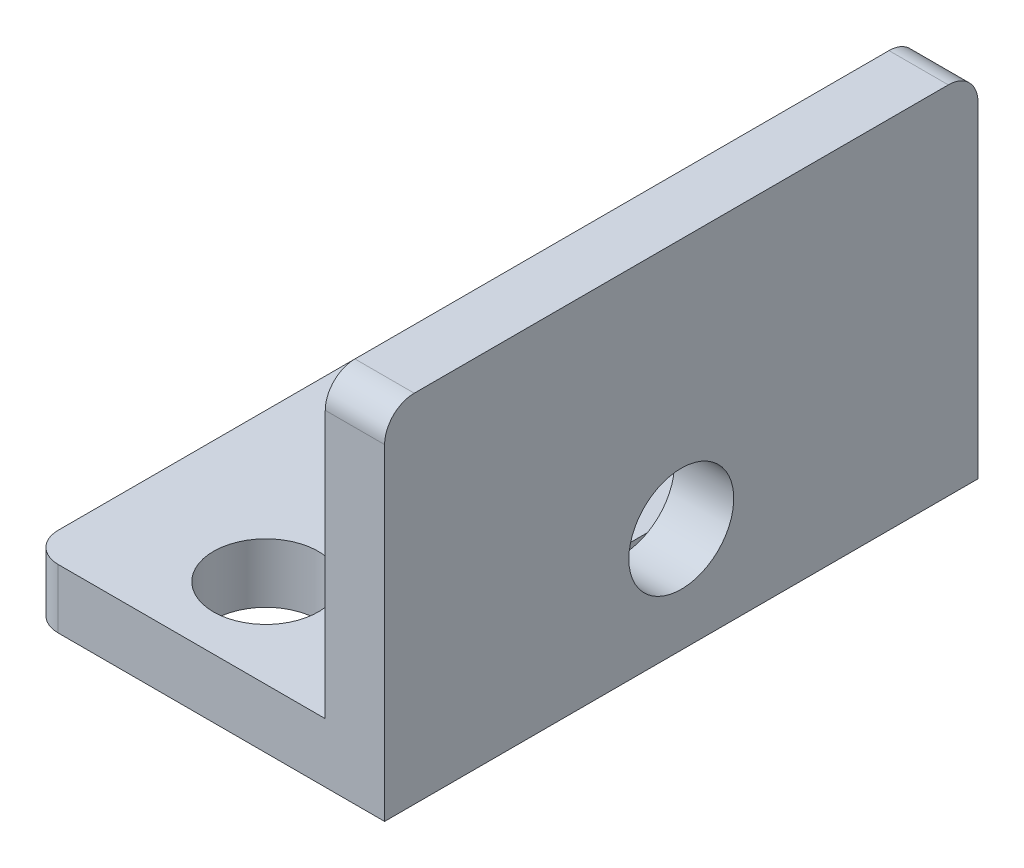
SolidWorks part; units mm, degrees
material "6061 Alloy"
ref_plane "Front" through (0, 0, 0) normal (0, 0, 1) x (1, 0, 0)
ref_plane "Top" through (0, 0, 0) normal (0, 1, 0) x (1, 0, 0)
ref_plane "Right" through (0, 0, 0) normal (1, 0, 0) x (0, 0, -1)
sketch "Sketch1" plane through (0, 0, 0) normal (0, 0, 1) x (1, 0, 0)
  line L0 (0, 0) -> (0, 19.05)
  line L1 (0, 19.05) -> (-3.175, 19.05)
  line L2 (-3.175, 19.05) -> (-3.175, 3.175)
  line L3 (-3.175, 3.175) -> (-19.05, 3.175)
  line L4 (-19.05, 3.175) -> (-19.05, 0)
  line L5 (-19.05, 0) -> (0, 0)
  dimension "D1" = 19.05
  dimension "D2" = 3.175
extrude "Boss-Extrude1" add sketch "Sketch1" along normal blind 31.75
hole_wizard "#10 Clearance Hole1" positions "Sketch2" profile "Sketch3" hole size "#10" standard "ANSI Inch"
sketch "Sketch2" plane through (0, 3.175, 0) normal (0, 1, 0) x (1, 0, 0)
  line L0 (-11.1125, 0) -> (-11.1125, -31.75) construction
  line L1 (-3.175, 0) -> (-19.05, 0) construction
  line L2 (-3.175, -31.75) -> (-19.05, -31.75) construction
  point P9 (-11.1125, -4.7625)
  point P11 (-11.1125, -26.9875)
  point P14 (-11.1125, -15.875)
  dimension "D1" = 11.1125
  dimension "D2" = 11.1125
sketch "Sketch3" plane through (-11.1125, 3.175, 26.9875) normal (1, 0, 0) x (0, 0, 1)
  line L0 (0, 0) -> (0, 27.0864)
  line L1 (0, 27.0864) -> (2.8067, 25.4)
  line L2 (2.8067, 25.4) -> (2.8067, 0)
  line L5 (2.8067, 0) -> (0, 0)
  line L10 (0, 27.0864) -> (-2.8067, 25.4) construction
  line L11 (0, -6.35) -> (0, 107.95) construction
  dimension "Hole Dia." = 5.6134
  dimension "Hole Depth" = 25.4
  dimension "Drill Angle" = 118
hole_wizard "#10 Clearance Hole2" positions "Sketch4" profile "Sketch5" hole size "#10" standard "ANSI Inch"
sketch "Sketch4" plane through (-3.175, 0, 0) normal (-1, 0, 0) x (0, 0, 1)
  line L0 (15.875, 19.05) -> (15.875, 3.175) construction
  line L1 (31.75, 19.05) -> (0, 19.05) construction
  line L2 (31.75, 3.175) -> (0, 3.175) construction
  line L3 (31.75, 0) -> (0, 0) construction
  point P9 (15.875, 5.6261)
  dimension "D1" = 5.6261
sketch "Sketch5" plane through (-3.175, 5.6261, 15.875) normal (0, 1, 0) x (0, 0, 1)
  line L0 (0, 0) -> (0, 27.0864)
  line L1 (0, 27.0864) -> (2.8067, 25.4)
  line L2 (2.8067, 25.4) -> (2.8067, 0)
  line L5 (2.8067, 0) -> (0, 0)
  line L10 (0, 27.0864) -> (-2.8067, 25.4) construction
  line L11 (0, -6.35) -> (0, 107.95) construction
  dimension "Hole Dia." = 5.6134
  dimension "Hole Depth" = 25.4
  dimension "Drill Angle" = 118
fillet "Fillet1" radius 1.5875 4 edges at (-19.05, 1.5875, 0) (-19.05, 1.5875, 31.75) (-1.5875, 19.05, 0) (-1.5875, 19.05, 31.75)
